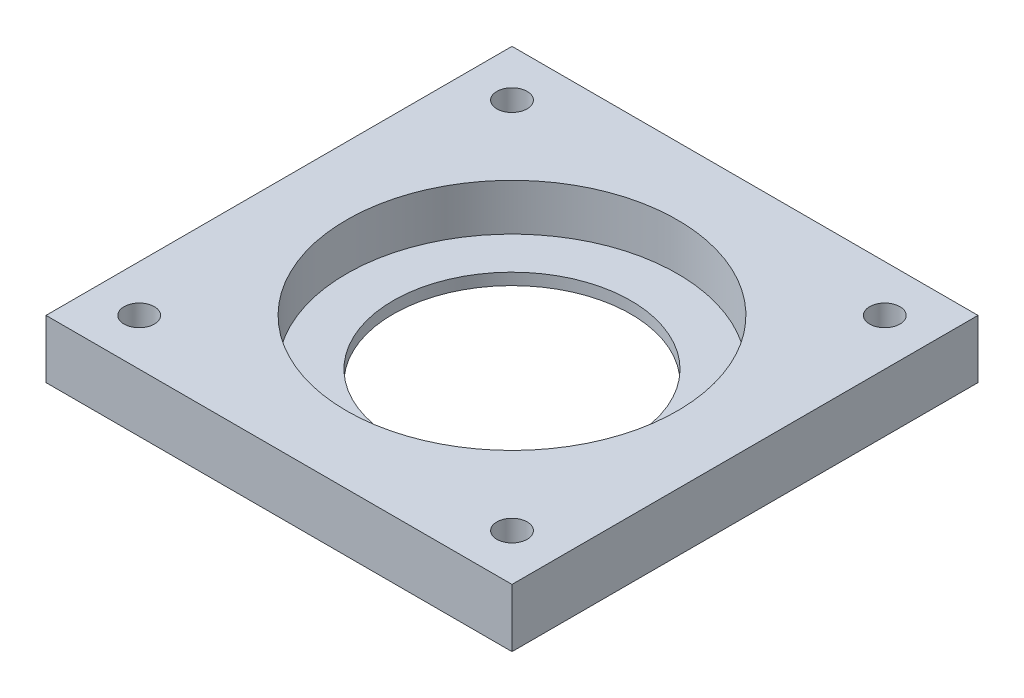
SolidWorks part; units mm, degrees
ref_plane "Alzado" through (0, 0, 0) normal (0, 0, 1) x (1, 0, 0)
ref_plane "Planta" through (0, 0, 0) normal (0, 1, 0) x (1, 0, 0)
ref_plane "Vista lateral" through (0, 0, 0) normal (1, 0, 0) x (0, 0, -1)
sketch "Croquis1" plane through (0, 0, 0) normal (0, 1, 0) x (1, 0, 0)
  line L1 (-50, 50) -> (50, 50)
  line L2 (-50, 50) -> (-50, -50)
  line L3 (-50, -50) -> (50, -50)
  line L4 (50, 50) -> (50, -50)
  line L5 (-50, 50) -> (50, -50) construction
  line L6 (-50, -50) -> (50, 50) construction
  point P0 (0, 0)
  point P2 (0, 0)
  dimension "D1" = 100
  dimension "D2" = 100
extrude "Saliente-Extruir1" add sketch "Croquis1" along normal blind 12.5
sketch "Croquis2" plane through (0, 12.5, 0) normal (0, 1, 0) x (1, 0, 0)
  circle A0 centre (0, 0) radius 35.5
  dimension "D1" = 71
extrude "Cortar-Extruir1" cut sketch "Croquis2" against normal blind 10
sketch "Croquis3" plane through (0, 2.5, 0) normal (0, 1, 0) x (1, 0, 0)
  circle A0 centre (0, 0) radius 25.5
  dimension "D1" = 51
extrude "Cortar-Extruir2" cut sketch "Croquis3" against normal through all
sketch "Croquis4" plane through (0, 12.5, 0) normal (0, 1, 0) x (1, 0, 0)
  line L1 (-40, -40) -> (40, -40)
  line L2 (-40, -40) -> (-40, 40)
  line L3 (-40, 40) -> (40, 40)
  line L4 (40, -40) -> (40, 40)
  line L5 (-40, -40) -> (40, 40) construction
  line L6 (-40, 40) -> (40, -40) construction
  circle A0 centre (40, 40) radius 3.25
  point P0 (0, 0)
  dimension "D3" = 6.5
  dimension "D2" = 80
extrude "Cortar-Extruir3" cut sketch "Croquis4" against normal through all contours L4 A0 L3 | L3 A0 L4
pattern_circular "MatrizC1" count 4 over 360 about axis through (0, 0, 0) along (0, 1, 0) of "Cortar-Extruir3"
